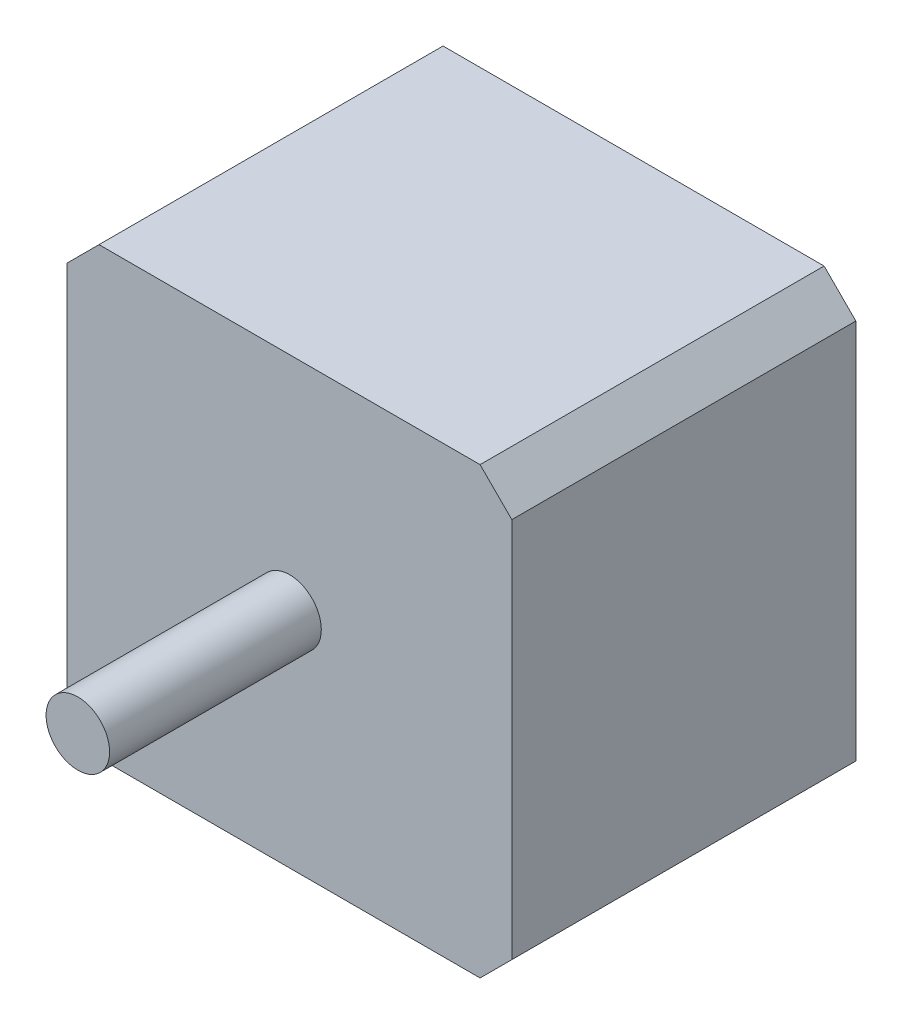
SolidWorks part; units mm, degrees
ref_plane "Front Plane" through (0, 0, 0) normal (1, 0, 0) x (0, 1, 0)
ref_plane "Top Plane" through (0, 0, 0) normal (0, 0, 1) x (0, 1, 0)
ref_plane "Right Plane" through (0, 0, 0) normal (0, 1, 0) x (-1, 0, 0)
sketch "Sketch1" plane through (0, 0, 0) normal (0, 0, 1) x (0, 1, 0)
  line L1 (-21, 21) -> (21, 21)
  line L2 (-21, 21) -> (-21, -21)
  line L3 (-21, -21) -> (21, -21)
  line L4 (21, 21) -> (21, -21)
  line L5 (-21, 21) -> (21, -21) construction
  line L6 (-21, -21) -> (21, 21) construction
  point P0 (0, 0)
  dimension "D1" = 42
  dimension "D2" = 42
extrude "Boss-Extrude1" add sketch "Sketch1" along normal blind 32.5
chamfer "Chamfer1" distance 3 angle 45 4 edges at (-21, 21, 16.25) (-21, -21, 16.25) (21, -21, 16.25) (21, 21, 16.25)
sketch "Sketch2" plane through (0, 0, 32.5) normal (0, 0, 1) x (1, 0, 0)
  circle A0 centre (0, 0) radius 3
  dimension "D1" = 6
extrude "Boss-Extrude2" add sketch "Sketch2" along normal blind 20
